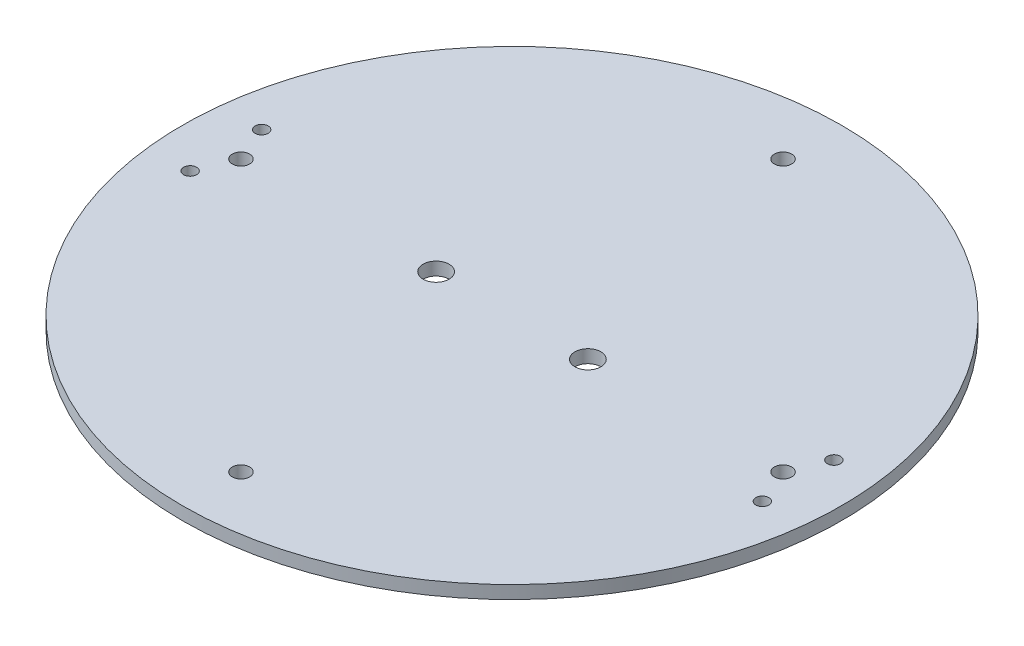
SolidWorks part; units mm, degrees
material "1060 Alloy"
ref_plane "Front Plane" through (0, 0, 0) normal (0, 0, 1) x (1, 0, 0)
ref_plane "Top Plane" through (0, 0, 0) normal (0, 1, 0) x (1, 0, 0)
ref_plane "Right Plane" through (0, 0, 0) normal (1, 0, 0) x (0, 0, -1)
sketch "Sketch1" plane through (0, 0, 0) normal (0, 1, 0) x (1, 0, 0)
  line L0 (-76, 0) -> (76, 0) construction
  line L1 (0, 76) -> (0, -76) construction
  line L2 (-65.9791, -8.25) -> (-65.9791, 8.25) construction
  circle A8 centre (0, 0) radius 76
  circle A10 centre (-65.9791, -8.25) radius 1.5
  circle A11 centre (-62.5, 0) radius 2
  circle A12 centre (-65.9791, 8.25) radius 1.5
  circle A13 centre (65.9791, 8.25) radius 1.5
  circle A14 centre (65.9791, -8.25) radius 1.5
  circle A15 centre (0, 62.5) radius 2
  circle A16 centre (62.5, 0) radius 2
  circle A17 centre (0, -62.5) radius 2
  circle A18 centre (17.5, 0) radius 3
  circle A19 centre (-17.5, 0) radius 3
  point P11 (-65.9791, 0)
  point P20 (0, 0)
  point P28 (0, 0)
  dimension "D1" = 4
  dimension "D2" = 3
  dimension "D3" = 3
  dimension "D4" = 152
  dimension "D5" = 62.5
  dimension "D6" = 16.5
  dimension "D7" = 65.9791
  dimension "D9" = 17.5
  dimension "D10" = 6
  dimension "D11" = 6
  dimension "D8" = 17.5
extrude "Boss-Extrude1" add sketch "Sketch1" along normal blind 3
sketch "Sketch2" plane through (0, 3, 0) normal (0, 1, 0) x (1, 0, 0)
  line L1 (-53.7401, 53.7401) -> (53.7401, 53.7401)
  line L2 (-53.7401, 53.7401) -> (-53.7401, -53.7401)
  line L3 (-53.7401, -53.7401) -> (53.7401, -53.7401)
  line L4 (53.7401, 53.7401) -> (53.7401, -53.7401)
  circle A0 centre (0, 0) radius 76 construction
